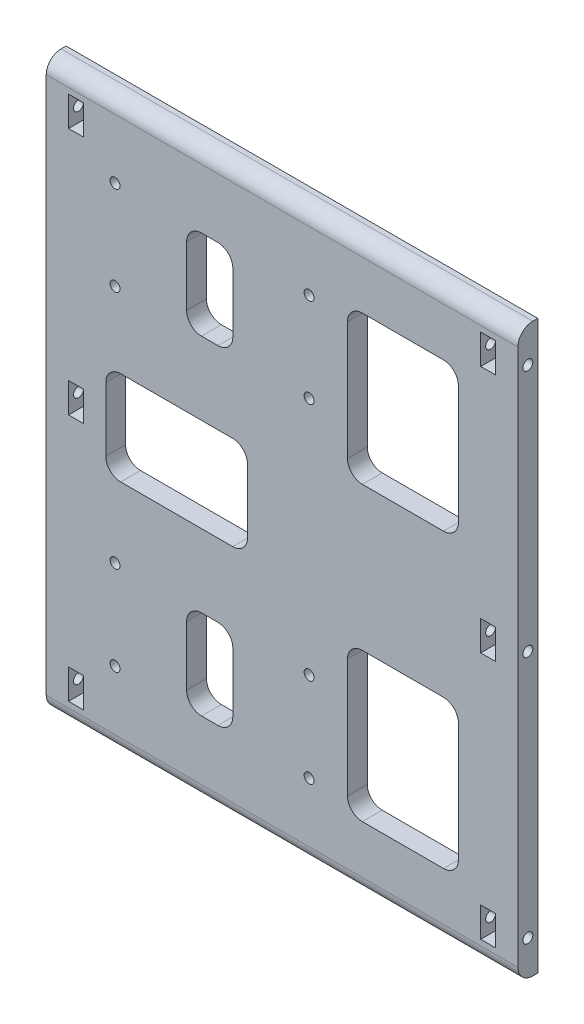
SolidWorks part; units mm, degrees
ref_plane "Plan de face" through (0, 0, 0) normal (0, 0, 1) x (1, 0, 0)
ref_plane "Plan de dessus" through (0, 0, 0) normal (0, 1, 0) x (1, 0, 0)
ref_plane "Plan de droite" through (0, 0, 0) normal (1, 0, 0) x (0, 0, -1)
sketch "Esquisse2" plane through (0, 0, 0) normal (0, 0, 1) x (1, 0, 0)
  line L0 (-47.54, 0) -> (47.54, 0) construction
  line L1 (-47.54, 57.15) -> (47.54, 57.15)
  line L2 (-47.54, 57.15) -> (-47.54, -57.15)
  line L3 (-47.54, -57.15) -> (47.54, -57.15)
  line L4 (47.54, 57.15) -> (47.54, -57.15)
  line L5 (-47.54, 57.15) -> (47.54, -57.15) construction
  line L6 (-47.54, -57.15) -> (47.54, 57.15) construction
  line L7 (-47.54, -24.15) -> (47.54, -24.15) construction
  line L8 (-47.54, -42.15) -> (47.54, -42.15) construction
  line L9 (-47.54, 42.15) -> (47.54, 42.15) construction
  line L10 (-47.54, 24.15) -> (47.54, 24.15) construction
  line L11 (35.54, 44.3867) -> (13.1772, 44.3867)
  line L12 (-9.9293, 42.15) -> (-19.2421, 42.15)
  line L13 (-9.9293, 42.15) -> (-9.9293, 24.15)
  line L14 (-9.9293, 24.15) -> (-19.2421, 24.15)
  line L15 (-19.2421, 42.15) -> (-19.2421, 24.15)
  line L16 (-9.9293, -24.15) -> (-19.2421, -24.15)
  line L17 (-9.9293, -24.15) -> (-9.9293, -42.15)
  line L18 (-9.9293, -42.15) -> (-19.2421, -42.15)
  line L19 (-19.2421, -24.15) -> (-19.2421, -42.15)
  line L20 (-6.9687, 9.4477) -> (-35.54, 9.4477)
  line L21 (-6.9687, 9.4477) -> (-6.9687, -9.4477)
  line L22 (-6.9687, -9.4477) -> (-35.54, -9.4477)
  line L23 (-35.54, 9.4477) -> (-35.54, -9.4477)
  line L24 (-6.9687, 9.4477) -> (-35.54, -9.4477) construction
  line L25 (-6.9687, -9.4477) -> (-35.54, 9.4477) construction
  line L26 (35.54, -14.4986) -> (13.1772, -14.4986)
  line L27 (35.54, -14.4986) -> (35.54, -44.3867)
  line L28 (35.54, -44.3867) -> (13.1772, -44.3867)
  line L29 (13.1772, -14.4986) -> (13.1772, -44.3867)
  line L30 (13.1772, 14.4986) -> (13.1772, 44.3867)
  line L31 (35.54, 14.4986) -> (13.1772, 14.4986)
  line L32 (35.54, 14.4986) -> (35.54, 44.3867)
  line L33 (41.54, -57.15) -> (41.54, 57.15) construction
  line L34 (0, -57.15) -> (0, 57.15) construction
  line L35 (43.04, -3) -> (43.04, 3)
  line L36 (40.04, -53) -> (43.04, -53)
  line L37 (40.04, -53) -> (40.04, -47)
  line L38 (40.04, -47) -> (43.04, -47)
  line L39 (43.04, -53) -> (43.04, -47)
  line L40 (40.04, -53) -> (43.04, -47) construction
  line L41 (40.04, -47) -> (43.04, -53) construction
  line L42 (40.04, 3) -> (43.04, 3)
  line L43 (40.04, -3) -> (40.04, 3)
  line L44 (40.04, -3) -> (43.04, -3)
  line L45 (43.04, 47) -> (43.04, 53)
  line L46 (40.04, 53) -> (43.04, 53)
  line L47 (40.04, 47) -> (40.04, 53)
  line L48 (40.04, 47) -> (43.04, 47)
  line L49 (-41.54, -57.15) -> (-41.54, 57.15) construction
  line L50 (-40.04, 53) -> (-43.04, 53)
  line L51 (-40.04, 47) -> (-40.04, 53)
  line L52 (-43.04, 47) -> (-43.04, 53)
  line L53 (-40.04, 47) -> (-43.04, 47)
  line L54 (-40.04, 3) -> (-43.04, 3)
  line L55 (-40.04, -3) -> (-43.04, -3)
  line L56 (-40.04, -3) -> (-40.04, 3)
  line L57 (-43.04, -3) -> (-43.04, 3)
  line L58 (-40.04, -53) -> (-43.04, -53)
  line L59 (-40.04, -53) -> (-40.04, -47)
  line L60 (-43.04, -53) -> (-43.04, -47)
  line L61 (-40.04, -47) -> (-43.04, -47)
  circle A0 centre (-33.6691, -42.15) radius 1
  circle A1 centre (5.4509, -42.15) radius 1
  circle A2 centre (5.4509, -24.15) radius 1
  circle A3 centre (-33.6691, -24.15) radius 1
  circle A4 centre (-33.6691, 24.15) radius 1
  circle A5 centre (5.4509, 24.15) radius 1
  circle A6 centre (5.4509, 42.15) radius 1
  circle A7 centre (-33.6691, 42.15) radius 1
  point P0 (0, 0)
  point P40 (-21.2543, 0)
  point P57 (41.54, -50)
  point P58 (41.54, -50)
  dimension "D5" = 2
  dimension "D1" = 114.3
  dimension "D2" = 95.08
  dimension "D3" = 18
  dimension "D4" = 15
  dimension "D7" = 39.12
  dimension "D8" = 15.3803
  dimension "D9" = 12
  dimension "D10" = 6
  dimension "D11" = 7.15
  dimension "D12" = 6
  dimension "D13" = 3
  dimension "D6" = 2
  dimension "D14" = 3
extrude "Boss.-Extru.1" add sketch "Esquisse2" along normal blind 4
fillet "Congé1" radius 3 20 edges at (-19.2421, 24.15, 2) (-35.54, -9.4477, 2) (-19.2421, -42.15, 2) (13.1772, -44.3867, 2) (13.1772, -14.4986, 2) (-19.2421, -24.15, 2) (-35.54, 9.4477, 2) (-19.2421, 42.15, 2) (-9.9293, 42.15, 2) (-6.9687, 9.4477, 2) (-9.9293, -24.15, 2) (35.54, -14.4986, 2) (35.54, -44.3867, 2) (-6.9687, -9.4477, 2) (-9.9293, 24.15, 2) (35.54, 14.4986, 2) (13.1772, 14.4986, 2) (13.1772, 44.3867, 2) (35.54, 44.3867, 2) (-9.9293, -42.15, 2)
sketch "Esquisse3" plane through (47.54, 0, 0) normal (1, 0, 0) x (0, 0, -1)
  line L0 (-2, 57.15) -> (-2, -57.15) construction
  line L1 (-4, 57.15) -> (0, 57.15) construction
  line L2 (-4, -57.15) -> (0, -57.15) construction
  circle A0 centre (-2, 50) radius 1
  circle A1 centre (-2, 0) radius 1
  circle A2 centre (-2, -50) radius 1
  dimension "D1" = 3
  dimension "D2" = 7.15
extrude "Enlèv. mat.-Extru.1" cut sketch "Esquisse3" against normal blind 10
sketch "Esquisse4" plane through (-47.54, 0, 0) normal (-1, 0, 0) x (0, 0, 1)
  line L0 (2, 57.15) -> (2, -57.15) construction
  line L1 (4, 57.15) -> (0, 57.15) construction
  line L2 (4, -57.15) -> (0, -57.15) construction
  circle A0 centre (2, 50) radius 1
  circle A1 centre (2, 0) radius 1
  circle A2 centre (2, -50) radius 1
  dimension "D1" = 7.15
  dimension "D2" = 3
extrude "Enlèv. mat.-Extru.2" cut sketch "Esquisse4" against normal blind 10
fillet "Congé2" radius 3 2 edges at (0, 57.15, 4) (0, -57.15, 4)
